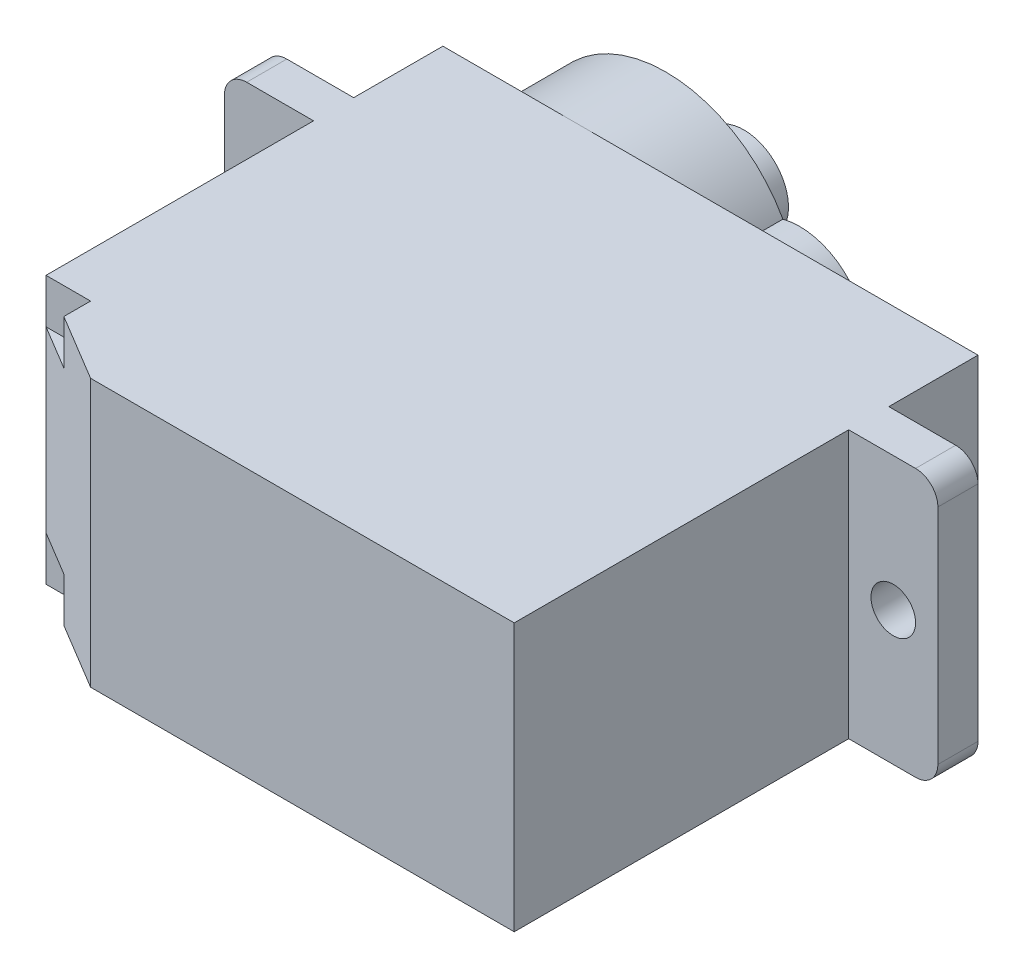
SolidWorks part; units mm, degrees
ref_plane "Спереди" through (0, 0, 0) normal (0, 0, 1) x (1, 0, 0)
ref_plane "Сверху" through (0, 0, 0) normal (0, 1, 0) x (1, 0, 0)
ref_plane "Справа" through (0, 0, 0) normal (1, 0, 0) x (0, 0, -1)
sketch "Эскиз1" plane through (0, 0, 0) normal (0, 0, 1) x (1, 0, 0)
  line L1 (-12, -6) -> (12, -6)
  line L2 (-12, -6) -> (-12, 6)
  line L3 (-12, 6) -> (12, 6)
  line L4 (12, -6) -> (12, 6)
  line L5 (-12, -6) -> (12, 6) construction
  line L6 (-12, 6) -> (12, -6) construction
  point P0 (0, 0)
extrude "Бобышка-Вытянуть1" add sketch "Эскиз1" along normal blind 12
sketch "Эскиз2" plane through (0, 0, 0) normal (0, 0, -1) x (-1, 0, 0)
  line L0 (12, 6) -> (15, 6)
  line L1 (12, -6) -> (15, -6)
  line L2 (16, -5) -> (16, 5)
  line L3 (-12, -6) -> (-15, -6)
  line L4 (-14, 0) -> (14, 0) construction
  line L6 (-12, 6) -> (-15, 6)
  line L7 (-16, 5) -> (-16, -5)
  line L8 (12, 6) -> (-12, 6)
  line L9 (12, -6) -> (-12, -6)
  arc A0 (-15, 6) -> (-16, 5) centre (-15, 5) ccw
  arc A1 (-15, -6) -> (-16, -5) centre (-15, -5) cw
  arc A2 (15, -6) -> (16, -5) centre (15, -5) ccw
  arc A3 (15, 6) -> (16, 5) centre (15, 5) cw
  circle A4 centre (14, 0) radius 1
  circle A5 centre (-14, 0) radius 1
  point P24 (0, 0)
  dimension "D1" = 1
extrude "Бобышка-Вытянуть2" add sketch "Эскиз2" along normal blind 1.8
sketch "Эскиз3" plane through (0, 0, -1.8) normal (0, 0, -1) x (-1, 0, 0)
  line L1 (-12, 6) -> (12, 6)
  line L2 (-12, 6) -> (-12, -6)
  line L3 (-12, -6) -> (12, -6)
  line L4 (12, 6) -> (12, -6)
  line L5 (-12, 6) -> (12, -6) construction
  line L6 (-12, -6) -> (12, 6) construction
  point P0 (0, 0)
extrude "Бобышка-Вытянуть3" add sketch "Эскиз3" along normal blind 4 contours L4 L3 L2 L1
sketch "Эскиз4" plane through (0, 0, -5.8) normal (0, 0, -1) x (-1, 0, 0)
  line L0 (12, 0) -> (6, 0) construction
  line L1 (12, 6) -> (12, -6) construction
  line L2 (0, 0) -> (-3, 0) construction
  circle A0 centre (6, 0) radius 6 construction
  arc A1 (0.75, -2.9047) -> (0.75, 2.9047) centre (0, 0) cw
  arc A2 (0.75, 2.9047) -> (0.75, -2.9047) centre (6, 0) cw
extrude "Бобышка-Вытянуть4" add sketch "Эскиз4" along normal blind 4 contours A2 A1
sketch "Эскиз5" plane through (0, 0, -9.8) normal (0, 0, -1) x (-1, 0, 0)
  circle A0 centre (6, 0) radius 2
extrude "Бобышка-Вытянуть5" add sketch "Эскиз5" along normal blind 3.5
sketch "Эскиз6" plane through (0, 0, 12) normal (0, 0, 1) x (1, 0, 0)
  line L0 (-12, 6) -> (-12, 4) construction
  line L4 (12, -6) -> (12, 6)
  line L5 (-12, -6) -> (12, 6) construction
  line L6 (-12, 6) -> (12, -6) construction
  line L7 (-12, 4) -> (-10, 4) construction
  line L8 (-10, 4) -> (-10, 6) construction
  line L9 (-12, -6) -> (-12, -4) construction
  line L10 (-12, -4) -> (-10, -4) construction
  line L11 (-10, -4) -> (-10, -6) construction
  line L12 (-10, -6) -> (-12, -6) construction
  line L13 (12, -6) -> (-10, -6)
  line L14 (-12, -4) -> (-12, 4)
  line L15 (-12, 4) -> (-10, 4)
  line L16 (-10, 4) -> (-10, 6)
  line L17 (-10, 6) -> (12, 6)
  line L18 (-10, -6) -> (-10, -4)
  line L19 (-10, -4) -> (-12, -4)
  point P4 (0, 0)
extrude "Бобышка-Вытянуть6" add sketch "Эскиз6" along normal blind 3
sketch "Эскиз8" plane through (0, 6, 0) normal (0, 1, 0) x (1, 0, 0)
  line L0 (-12, -12) -> (-7, -12) construction
  line L1 (-7, -12) -> (-7, -15) construction
  line L2 (12, -15) -> (-10, -15) construction
  line L3 (-7, -15) -> (-12, -12)
  line L4 (-12, -12) -> (-12, -15)
  line L5 (-12, -15) -> (-7, -15)
extrude "Вырез-Вытянуть1" cut sketch "Эскиз8" against normal blind 12
